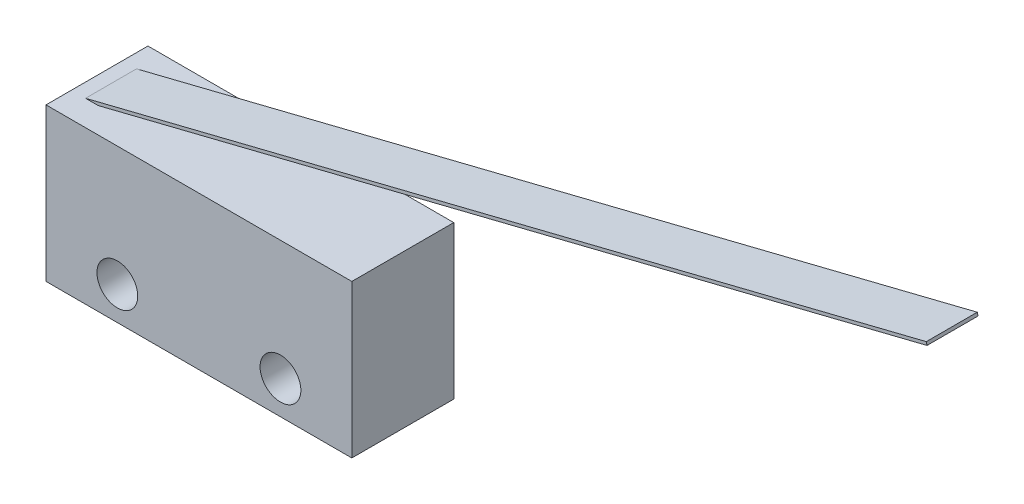
SolidWorks part; units mm, degrees
ref_plane "Front" through (0, 0, 0) normal (0, 0, 1) x (1, 0, 0)
ref_plane "Top" through (0, 0, 0) normal (0, 1, 0) x (1, 0, 0)
ref_plane "Right" through (0, 0, 0) normal (1, 0, 0) x (0, 0, -1)
sketch "Sketch1" plane through (0, 0, 0) normal (0, 0, 1) x (1, 0, 0)
  line L1 (0, 0) -> (19.05, 0)
  line L2 (0, 0) -> (0, 9.525)
  line L3 (0, 9.525) -> (19.05, 9.525)
  line L4 (19.05, 0) -> (19.05, 9.525)
  dimension "D1" = 19.05
  dimension "D2" = 9.525
extrude "Boss-Extrude1" add sketch "Sketch1" along normal blind 6.35
sketch "Sketch2" plane through (0, 0, 0) normal (0, 0, 1) x (1, 0, 0)
  line L0 (0.8756, 9.525) -> (53.2474, 22.5827)
  line L1 (19.05, 9.525) -> (0, 9.525) construction
  line L2 (53.2474, 22.5827) -> (53.2934, 22.3979)
  line L3 (53.2934, 22.3979) -> (1.6631, 9.525)
  line L4 (0.8756, 9.525) -> (1.6631, 9.525)
  dimension "D1" = 53.975
  dimension "D2" = 0.1905
  dimension "D3" = 14
extrude "Boss-Extrude2" add sketch "Sketch2" along normal blind 3.175 from offset 1.5875
sketch "Sketch3" plane through (0, 0, 6.35) normal (0, 0, 1) x (1, 0, 0)
  line L0 (3.4925, 0) -> (-3.4925, 0) construction
  line L1 (0, -3.4925) -> (0, 3.4925) construction
  line L2 (9.525, 9.525) -> (9.525, 0) construction
  line L3 (19.05, 9.525) -> (0, 9.525) construction
  circle A0 centre (4.445, 2.0638) radius 1.27
  circle A1 centre (14.605, 2.0638) radius 1.27
  dimension "D1" = 2.54
  dimension "D2" = 2.0638
  dimension "D3" = 4.445
extrude "Cut-Extrude1" cut sketch "Sketch3" against normal through all contours A1 | A0
